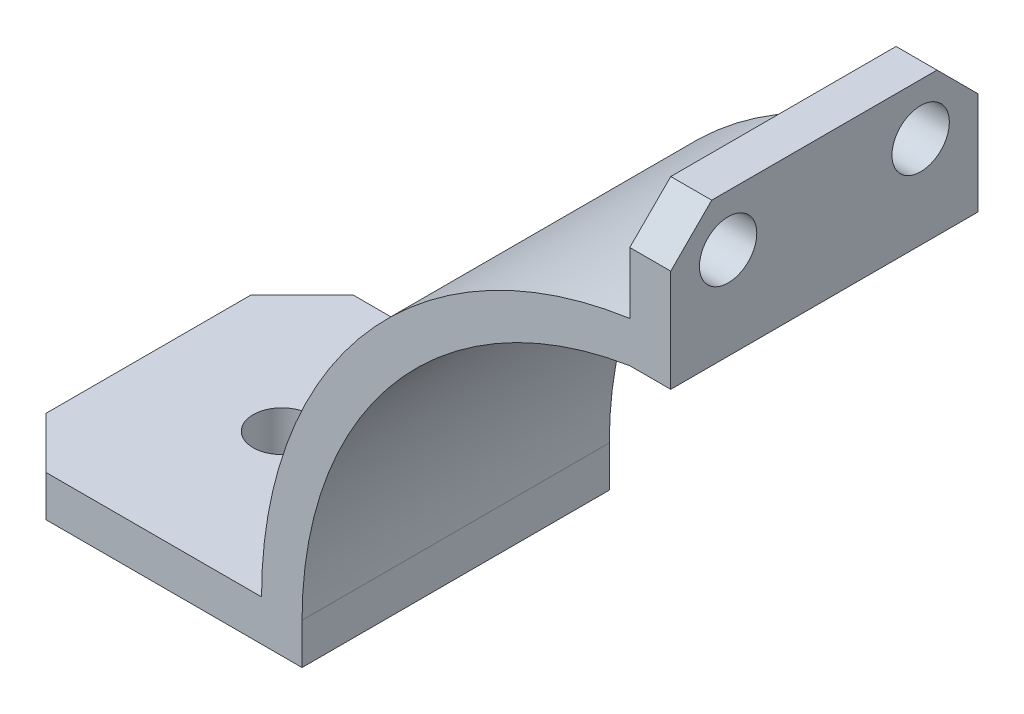
SolidWorks part; units mm, degrees
ref_plane "Front Plane" through (0, 0, 0) normal (0, 0, 1) x (1, 0, 0)
ref_plane "Top Plane" through (0, 0, 0) normal (0, 1, 0) x (1, 0, 0)
ref_plane "Right Plane" through (0, 0, 0) normal (1, 0, 0) x (0, 0, -1)
sketch "Sketch1" plane through (0, 0, 0) normal (0, 0, 1) x (1, 0, 0)
  line L0 (0, 0) -> (0, 50000) construction
  line L2 (-19, 0) -> (-19, -2)
  line L3 (-19, -2) -> (-34, -2)
  line L4 (-34, -2) -> (-34, 0)
  line L5 (-34, 0) -> (-20.9773, 0)
  line L6 (-3, 20.7617) -> (-3, 25.7617)
  line L7 (-3, 25.7617) -> (-1, 25.7617)
  line L8 (-1, 25.7617) -> (-1, 18.7617)
  line L9 (-1, 18.7617) -> (-3, 18.7617)
  arc A0 (-19, 0) -> (-3, 18.7617) centre (0, 0) cw
  arc A1 (-20.9773, 0) -> (-3, 20.7617) centre (0, 0) cw
  dimension "D2" = 19
  dimension "D1" = 2
  dimension "D3" = 15
  dimension "D4" = 2
  dimension "D5" = 2
  dimension "D6" = 7
  dimension "D7" = 1
extrude "Boss-Extrude1" add sketch "Sketch1" along normal blind 15
chamfer "Chamfer1" distance 2.5 2 edges at (-34, -1, 0) (-34, -1, 15)
sketch "Sketch2" plane through (-3, 0, 0) normal (-1, 0, 0) x (0, 0, 1)
  line L0 (15, 25.7617) -> (15, 20.7617) construction
  line L1 (0, 25.7617) -> (0, 20.7617) construction
  circle A0 centre (2.8, 23.2617) radius 1.4
  circle A1 centre (12.2, 23.2617) radius 1.4
  point P8 (0, 23.2617)
  dimension "D1" = 2.8
  dimension "D2" = 2.8
  dimension "D3" = 2.8
extrude "Cut-Extrude1" cut sketch "Sketch2" against normal blind 15
chamfer "Chamfer2" distance 2 angle 45 2 edges at (-2, 25.7617, 15) (-2, 25.7617, 0)
sketch "Sketch3" plane through (0, 0, 0) normal (0, 1, 0) x (1, 0, 0)
  line L0 (-34, -12.5) -> (-34, -2.5) construction
  line L2 (-20.9773, 0) -> (-34, 0.1) construction
  line L3 (48.1877, 0.1) -> (-41.7286, 0.1) construction
  circle A0 centre (-27.4886, -7.5) radius 1.4
  point P2 (-27.4886, 0.05)
  point P5 (-34, -7.5)
  dimension "D1" = 2.8
extrude "Cut-Extrude2" cut sketch "Sketch3" against normal through all contours A0
